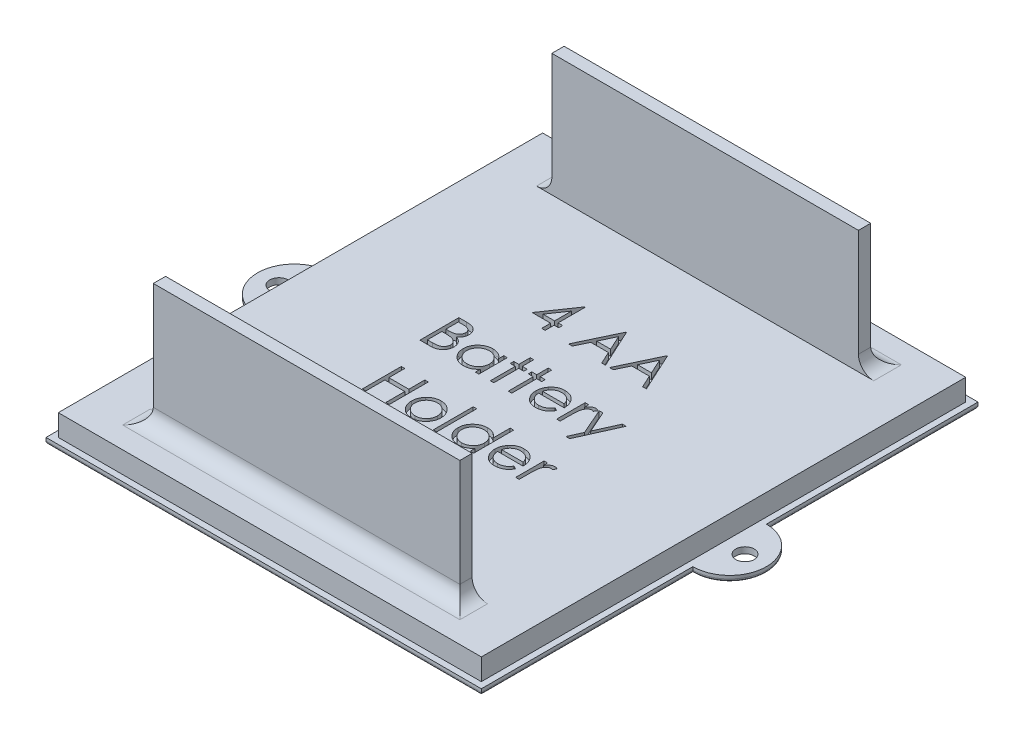
SolidWorks part; units mm, degrees
other "Markup1"
sketch "Sketch11" plane through (-41.5, 7, -35.5) normal (0, 1, 0) x (1, 0, 0)
sketch "Sketch12" plane through (-41.5, 7, -35.5) normal (0, 1, 0) x (1, 0, 0)
sketch "Sketch13" plane through (-41.5, 7, -35.5) normal (0, 1, 0) x (1, 0, 0)
sketch "Sketch15" plane through (-41.5, 7, -35.5) normal (0, 1, 0) x (1, 0, 0)
sketch "Sketch16" plane through (-41.5, 7, -35.5) normal (0, 1, 0) x (1, 0, 0)
sketch "Sketch17" plane through (-41.5, 7, -35.5) normal (0, 1, 0) x (1, 0, 0)
sketch "Sketch18" plane through (-41.5, 7, -35.5) normal (0, 1, 0) x (1, 0, 0)
sketch "Sketch19" plane through (-41.5, 7, -35.5) normal (0, 1, 0) x (1, 0, 0)
sketch "Sketch20" plane through (-41.5, 12, -35.5) normal (0, 1, 0) x (1, 0, 0)
sketch "Sketch21" plane through (-41.5, 12, -35.5) normal (0, 1, 0) x (1, 0, 0)
sketch "Sketch22" plane through (-41.5, 12, -35.5) normal (0, 1, 0) x (1, 0, 0)
sketch "Sketch31" plane through (-41.5, 25.5, -40.5) normal (0, 1, 0) x (1, 0, 0)
sketch "Sketch32" plane through (-41.5, 25.5, -40.5) normal (0, 1, 0) x (1, 0, 0)
sketch "Sketch38" plane through (-41.5, 25.5, -40.5) normal (0, 1, 0) x (1, 0, 0)
sketch "Sketch39" plane through (-41.5, 25.5, -40.5) normal (0, 1, 0) x (1, 0, 0)
sketch "Sketch40" plane through (-41.5, 25.5, -40.5) normal (0, 1, 0) x (1, 0, 0)
sketch "Sketch41" plane through (-41.5, 24.5, -40.5) normal (0, 1, 0) x (1, 0, 0)
sketch "Sketch48" plane through (-41.5, 24.5, -40.5) normal (0, 1, 0) x (1, 0, 0)
sketch "Sketch49" plane through (-41.5, 24.5, -40.5) normal (0, 1, 0) x (1, 0, 0)
sketch "Sketch50" plane through (-41.5, 24.5, -40.5) normal (0, 1, 0) x (1, 0, 0)
ref_plane "Front Plane" through (0, 0, 0) normal (0, 0, 1) x (1, 0, 0)
ref_plane "Top Plane" through (0, 0, 0) normal (0, 1, 0) x (1, 0, 0)
ref_plane "Right Plane" through (0, 0, 0) normal (1, 0, 0) x (0, 0, -1)
sketch "Sketch1" plane through (0, 0, 0) normal (0, 1, 0) x (1, 0, 0)
  line L1 (-35.5, -40.5) -> (35.5, -40.5)
  line L2 (-35.5, -40.5) -> (-35.5, 40.5)
  line L3 (-35.5, 40.5) -> (35.5, 40.5)
  line L4 (35.5, -40.5) -> (35.5, 40.5)
  line L5 (-35.5, -40.5) -> (35.5, 40.5) construction
  line L6 (-35.5, 40.5) -> (35.5, -40.5) construction
  point P0 (0, 0)
  dimension "D1" = 81
  dimension "D2" = 71
extrude "Boss-Extrude1" add sketch "Sketch1" along normal blind 4.5
sketch "text" plane through (0, 4.5, 0) normal (0, 1, 0) x (1, 0, 0)
  line L0 (-35.4043, 11.8177) -> (35.5957, 11.8177) construction
  text T0 "4 AA\r\nBattery \r\nHolder" font "Century Gothic" height in points 24
extrude "Cut-Extrude1" cut sketch "text" against normal blind 1
sketch "Sketch4" plane through (0, 4.5, 0) normal (0, 1, 0) x (1, 0, 0)
  line L0 (-35.5, 40.5) -> (-35.5, -40.5) construction
  line L1 (-35.5, 6) -> (-35.5, -6)
  arc A0 (-35.5, 6) -> (-35.5, -6) centre (-35.5, 0) ccw
  dimension "D1" = 6
extrude "Boss-Extrude3" add sketch "Sketch4" against normal up to surface (4.5 mm away) up to face at (0, 0, 0)
sketch "Sketch5" plane through (0, 4.5, 0) normal (0, 1, 0) x (1, 0, 0)
  line L0 (-35.5, 40.5) -> (-35.5, 6) construction
  circle A0 centre (-38, 0) radius 1.5
  dimension "D1" = 3
  dimension "D2" = 2.5
extrude "Cut-Extrude2" cut sketch "Sketch5" against normal up to surface (4.5 mm away) up to face at (-12.8333, 0, 0)
mirror "Mirror3" about plane through (0, 0, 0) normal (1, 0, 0) of "Boss-Extrude3", "Cut-Extrude2"
sketch "Sketch9" plane through (0, 4.5, 0) normal (0, 1, 0) x (1, 0, 0)
  line L0 (35.5, 40.5) -> (-35.5, 40.5) construction
  line L1 (-25, 33.5) -> (25, 33.5)
  line L2 (-25, 33.5) -> (-25, 31.5)
  line L3 (-25, 31.5) -> (25, 31.5)
  line L4 (25, 33.5) -> (25, 31.5)
  line L5 (-2.475, 0) -> (2.475, 0) construction
  point P5 (0, 33.5)
  point P8 (0, 40.5)
  dimension "D1" = 50
  dimension "D2" = 2
  dimension "D3" = 31.5
extrude "top track" add sketch "Sketch9" along normal blind 20 contours L2 L1 L4 L3
sketch "Sketch51" plane through (0, 4.5, 0) normal (0, 1, 0) x (1, 0, 0)
  line L0 (-35.5, 40.5) -> (-35.5, 6) construction
  line L1 (34.5, 39.5) -> (-34.5, 39.5)
  line L2 (34.5, 39.5) -> (34.5, -39.5)
  line L3 (34.5, -39.5) -> (-34.5, -39.5)
  line L4 (-34.5, 39.5) -> (-34.5, -39.5)
  line L5 (34.5, 39.5) -> (-34.5, -39.5) construction
  line L6 (34.5, -39.5) -> (-34.5, 39.5) construction
  line L7 (35.5, 40.5) -> (-35.5, 40.5) construction
  line L8 (-44.5, 49.5) -> (-44.5, -49.5)
  line L9 (44.5, -49.5) -> (-44.5, -49.5)
  line L10 (44.5, 49.5) -> (44.5, -49.5)
  line L11 (44.5, 49.5) -> (-44.5, 49.5)
  point P0 (0, 0)
  dimension "D1" = 1
  dimension "D2" = 1
  dimension "D3" = 10
extrude "Cut-Extrude25" cut sketch "Sketch51" against normal blind 3.5
fillet "Fillet2" radius 0.5 8 edges at (-35.5, 0, -23.25) (-41.5, 0, 0) (-35.5, 0, 23.25) (0, 0, 40.5) (35.5, 0, 23.25) (41.5, 0, 0) (35.5, 0, -23.25) (0, 0, -40.5)
fillet "Fillet3" radius 2.5 3 edges at (-25, 4.5, -32.5) (0, 4.5, -33.5) (25, 4.5, -32.5)
mirror "Mirror4" about plane through (0, 0, 0) normal (0, 0, 1) of "Fillet3", "top track"
equation "\"Screw_Diameter\"=3"
